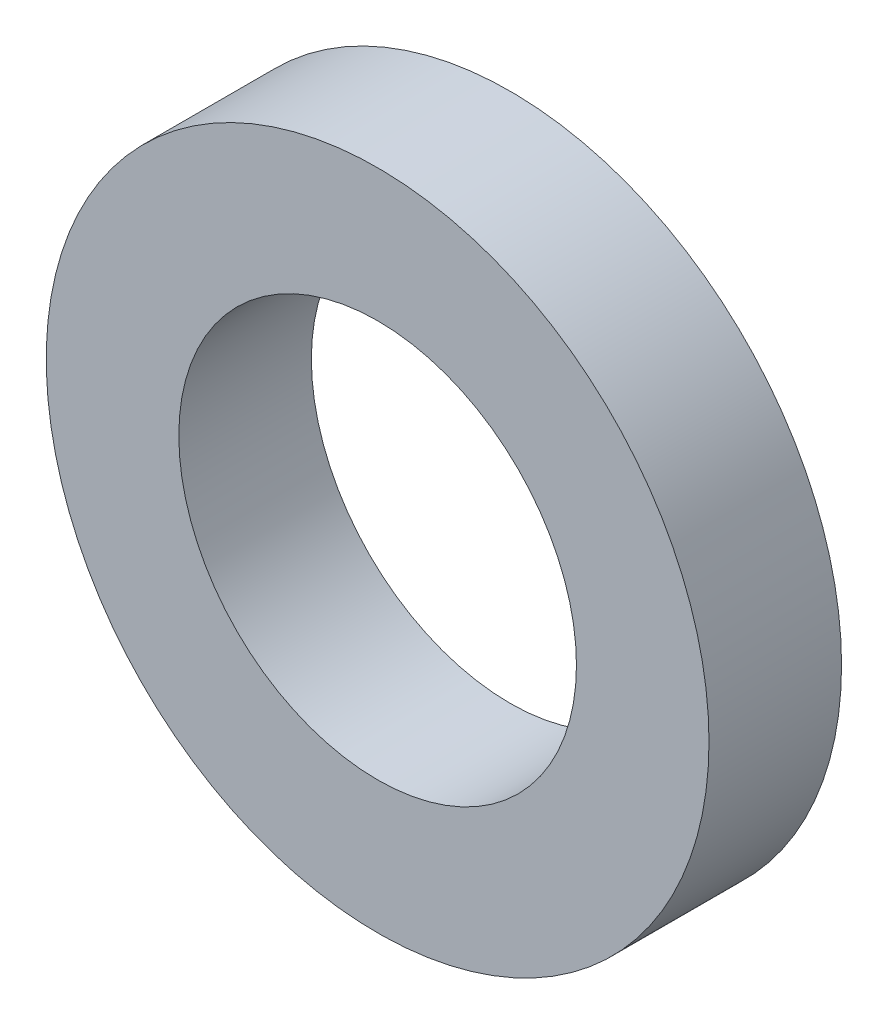
SolidWorks part; units mm, degrees
ref_plane "정면" through (0, 0, 0) normal (0, 0, 1) x (1, 0, 0)
ref_plane "윗면" through (0, 0, 0) normal (0, 1, 0) x (1, 0, 0)
ref_plane "우측면" through (0, 0, 0) normal (1, 0, 0) x (0, 0, -1)
sketch "스케치1" plane through (0, 0, 0) normal (0, 0, 1) x (1, 0, 0)
  circle A0 centre (0, 0) radius 1.5
  circle A1 centre (0, 0) radius 2.5
extrude "돌출1" add sketch "스케치1" along normal blind 1
